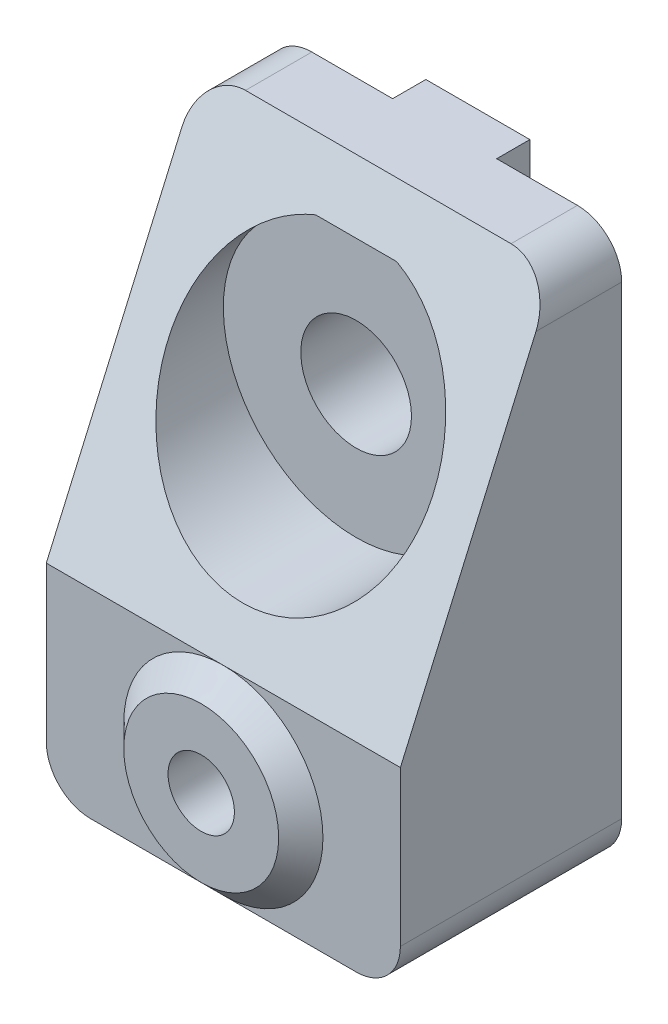
SolidWorks part; units mm, degrees
material "ABS"
ref_plane "Plan de face" through (0, 0, 0) normal (0, 0, 1) x (1, 0, 0)
ref_plane "Plan de dessus" through (0, 0, 0) normal (0, 1, 0) x (1, 0, 0)
ref_plane "Plan de droite" through (0, 0, 0) normal (1, 0, 0) x (0, 0, -1)
sketch "Esquisse1" plane through (0, 0, 0) normal (0, 1, 0) x (1, 0, 0)
  line L0 (2.35, 0) -> (8, 0)
  line L1 (-2.35, 1.5) -> (2.35, 1.5)
  line L2 (-2.35, 1.5) -> (-2.35, 0)
  line L3 (-2.35, 0) -> (2.35, 0) construction
  line L4 (2.35, 1.5) -> (2.35, 0)
  line L5 (-8, 0) -> (-2.35, 0)
  line L6 (-8, 0) -> (-8, -10)
  line L9 (-8, -10) -> (8, -10)
  line L10 (8, -10) -> (8, 0)
  dimension "D1" = 8
  dimension "D4" = 4.7
  dimension "D5" = 1.5
  dimension "D9" = 10
extrude "Boss.-Extru.1" add sketch "Esquisse1" along normal blind 8 and the other way blind 17
sketch "Esquisse2" plane through (-1.3724, 0, 0) normal (0, 0, 1) x (1, 0, 0)
  circle A0 centre (1.3724, 0) radius 2.5
  dimension "D1" = 5
extrude "Enlèv. mat.-Extru.1" cut sketch "Esquisse2" against normal through all both and the other way through all
sketch "Esquisse3" plane through (0, 0, 0) normal (0, 0, 1) x (1, 0, 0)
  circle A0 centre (0, 0) radius 6
  dimension "D1" = 12
extrude "Enlèv. mat.-Extru.2" cut sketch "Esquisse3" along normal through all from offset 4
sketch "Esquisse5" plane through (-2.35, 0, 0) normal (-1, 0, 0) x (0, 0, 1)
  line L0 (-1.5, 8) -> (-1.5, 0.8529) construction
  line L1 (-1.5, 2) -> (0, 2)
  line L2 (-1.5, 2) -> (-1.5, -2)
  line L3 (-1.5, -2) -> (0, -2)
  line L4 (0, 2) -> (0, -2)
  dimension "D1" = 4
extrude "Enlèv. mat.-Extru.3" cut sketch "Esquisse5" against normal through all
sketch "Esquisse6" plane through (0, 0, 10) normal (0, 0, 1) x (1, 0, 0)
  line L0 (-8, -17) -> (8, -17) construction
  circle A0 centre (0, -12.5) radius 4.5
  dimension "D1" = 9
extrude "Boss.-Extru.2" add sketch "Esquisse6" along normal blind 1 draft 45
sketch "Esquisse7" plane through (0, 0, 11) normal (0, 0, 1) x (1, 0, 0)
  circle A0 centre (0, -12.5) radius 1.5
  circle A1 centre (0, -12.5) radius 3.5 construction
  dimension "D1" = 3
extrude "Enlèv. mat.-Extru.4" cut sketch "Esquisse7" against normal through all
fillet "Congé1" radius 2 4 edges at (8, 8, 5) (8, -17, 5) (-8, -17, 5) (-8, 8, 5)
sketch "Esquisse8" plane through (-8, 0, 0) normal (-1, 0, 0) x (0, 0, 1)
  line L0 (3, 8) -> (10, -8)
  line L1 (0, 8) -> (10, 8) construction
  line L2 (10, -8) -> (10, 8)
  line L3 (10, 8) -> (3, 8)
  line L4 (0, 2) -> (0, 8) construction
  dimension "D1" = 3
extrude "Enlèv. mat.-Extru.5" cut sketch "Esquisse8" against normal through all
